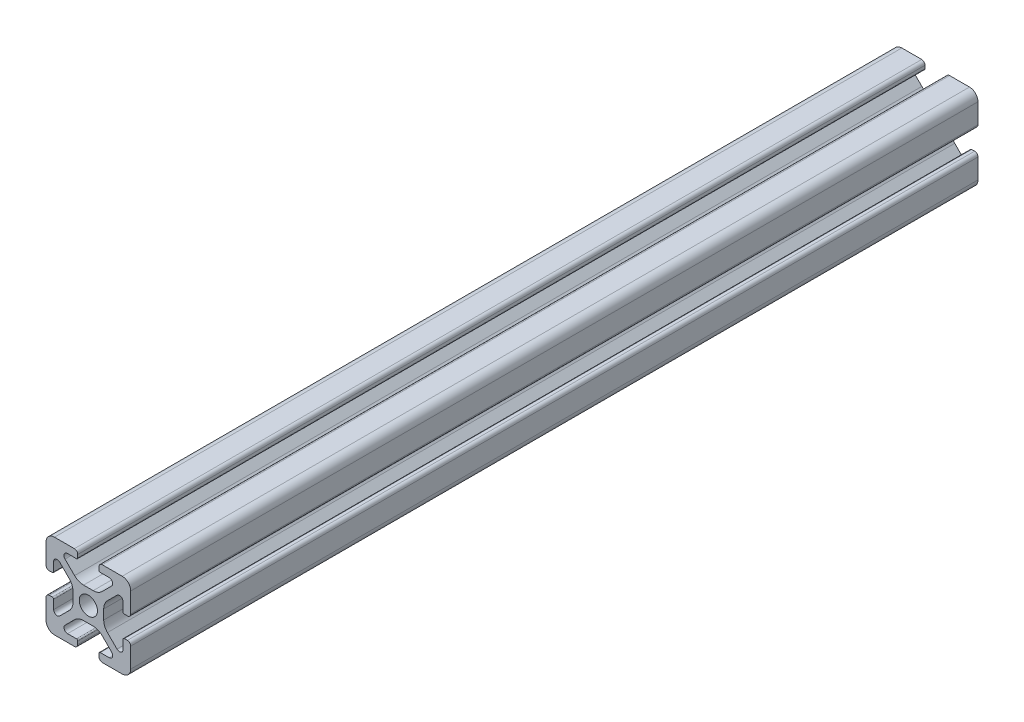
SolidWorks part; units mm, degrees
material "6061 Alloy"
ref_plane "Front Plane" through (0, 0, 0) normal (0, 0, 1) x (1, 0, 0)
ref_plane "Top Plane" through (0, 0, 0) normal (0, 1, 0) x (1, 0, 0)
ref_plane "Right Plane" through (0, 0, 0) normal (1, 0, 0) x (0, 0, -1)
sketch "Sketch1" plane through (0, 0, 0) normal (0, 0, 1) x (1, 0, 0)
  line L2 (-9.9949, 7.9883) -> (-9.9949, 3.2893)
  line L3 (-7.9883, 9.9949) -> (-3.2893, 9.9949)
  line L4 (-2.5019, 9.2075) -> (-2.5019, 8.4963)
  line L5 (-2.8067, 8.1915) -> (-4.9149, 8.1915)
  line L6 (-5.5076, 6.7606) -> (-3.2528, 4.5058)
  line L7 (-6.7606, 5.5076) -> (-4.5058, 3.2528)
  line L8 (-8.1915, 4.9149) -> (-8.1915, 2.8067)
  line L9 (-8.4963, 2.5019) -> (-9.2075, 2.5019)
  line L11 (-1.1334, 3.6279) -> (1.1334, 3.6279)
  line L12 (-3.6279, 1.1334) -> (-3.6279, -1.1334)
  line L13 (8.4963, 2.5019) -> (9.2075, 2.5019)
  line L14 (8.1915, 4.9149) -> (8.1915, 2.8067)
  line L15 (9.9949, 7.9883) -> (9.9949, 3.2893)
  line L16 (7.9883, 9.9949) -> (3.2893, 9.9949)
  line L17 (2.5019, 9.2075) -> (2.5019, 8.4963)
  line L18 (2.8067, 8.1915) -> (4.9149, 8.1915)
  line L19 (3.6279, 1.1334) -> (3.6279, -1.1334)
  line L20 (5.5076, 6.7606) -> (3.2528, 4.5058)
  line L21 (6.7606, 5.5076) -> (4.5058, 3.2528)
  line L22 (-8.4963, -2.5019) -> (-9.2075, -2.5019)
  line L23 (-8.1915, -4.9149) -> (-8.1915, -2.8067)
  line L24 (-6.7606, -5.5076) -> (-4.5058, -3.2528)
  line L25 (-5.5076, -6.7606) -> (-3.2528, -4.5058)
  line L26 (-2.8067, -8.1915) -> (-4.9149, -8.1915)
  line L27 (-2.5019, -9.2075) -> (-2.5019, -8.4963)
  line L28 (-7.9883, -9.9949) -> (-3.2893, -9.9949)
  line L29 (-9.9949, -7.9883) -> (-9.9949, -3.2893)
  line L30 (9.9949, -7.9883) -> (9.9949, -3.2893)
  line L31 (7.9883, -9.9949) -> (3.2893, -9.9949)
  line L32 (2.5019, -9.2075) -> (2.5019, -8.4963)
  line L33 (2.8067, -8.1915) -> (4.9149, -8.1915)
  line L34 (5.5076, -6.7606) -> (3.2528, -4.5058)
  line L35 (6.7606, -5.5076) -> (4.5058, -3.2528)
  line L36 (8.1915, -4.9149) -> (8.1915, -2.8067)
  line L37 (8.4963, -2.5019) -> (9.2075, -2.5019)
  line L38 (-1.1334, -3.6279) -> (1.1334, -3.6279)
  circle A0 centre (0, 0) radius 2.1463
  arc A1 (-9.9949, 7.9883) -> (-7.9883, 9.9949) centre (-7.9883, 7.9883) cw
  arc A2 (-6.7606, 5.5076) -> (-8.1915, 4.9149) centre (-7.3533, 4.9149) ccw
  arc A3 (-4.9149, 8.1915) -> (-5.5076, 6.7606) centre (-4.9149, 7.3533) ccw
  arc A4 (-3.2893, 9.9949) -> (-2.5019, 9.2075) centre (-3.2893, 9.2075) cw
  arc A5 (-9.9949, 3.2893) -> (-9.2075, 2.5019) centre (-9.2075, 3.2893) ccw
  arc A6 (-8.1915, 2.8067) -> (-8.4963, 2.5019) centre (-8.4963, 2.8067) cw
  arc A7 (-2.5019, 8.4963) -> (-2.8067, 8.1915) centre (-2.8067, 8.4963) cw
  arc A8 (-1.1334, 3.6279) -> (-3.2528, 4.5058) centre (-1.1334, 6.6251) cw
  arc A9 (-3.6279, 1.1334) -> (-4.5058, 3.2528) centre (-6.6251, 1.1334) ccw
  arc A10 (8.1915, 2.8067) -> (8.4963, 2.5019) centre (8.4963, 2.8067) ccw
  arc A11 (9.9949, 3.2893) -> (9.2075, 2.5019) centre (9.2075, 3.2893) cw
  arc A12 (9.9949, 7.9883) -> (7.9883, 9.9949) centre (7.9883, 7.9883) ccw
  arc A13 (3.2893, 9.9949) -> (2.5019, 9.2075) centre (3.2893, 9.2075) ccw
  arc A14 (2.5019, 8.4963) -> (2.8067, 8.1915) centre (2.8067, 8.4963) ccw
  arc A15 (1.1334, 3.6279) -> (3.2528, 4.5058) centre (1.1334, 6.6251) ccw
  arc A16 (3.6279, 1.1334) -> (4.5058, 3.2528) centre (6.6251, 1.1334) cw
  arc A17 (6.7606, 5.5076) -> (8.1915, 4.9149) centre (7.3533, 4.9149) cw
  arc A18 (4.9149, 8.1915) -> (5.5076, 6.7606) centre (4.9149, 7.3533) cw
  arc A19 (-3.6279, -1.1334) -> (-4.5058, -3.2528) centre (-6.6251, -1.1334) cw
  arc A20 (-1.1334, -3.6279) -> (-3.2528, -4.5058) centre (-1.1334, -6.6251) ccw
  arc A21 (-2.5019, -8.4963) -> (-2.8067, -8.1915) centre (-2.8067, -8.4963) ccw
  arc A22 (-8.1915, -2.8067) -> (-8.4963, -2.5019) centre (-8.4963, -2.8067) ccw
  arc A23 (-9.9949, -3.2893) -> (-9.2075, -2.5019) centre (-9.2075, -3.2893) cw
  arc A24 (-3.2893, -9.9949) -> (-2.5019, -9.2075) centre (-3.2893, -9.2075) ccw
  arc A25 (-4.9149, -8.1915) -> (-5.5076, -6.7606) centre (-4.9149, -7.3533) cw
  arc A26 (-6.7606, -5.5076) -> (-8.1915, -4.9149) centre (-7.3533, -4.9149) cw
  arc A27 (-9.9949, -7.9883) -> (-7.9883, -9.9949) centre (-7.9883, -7.9883) ccw
  arc A28 (9.9949, -7.9883) -> (7.9883, -9.9949) centre (7.9883, -7.9883) cw
  arc A29 (6.7606, -5.5076) -> (8.1915, -4.9149) centre (7.3533, -4.9149) ccw
  arc A30 (4.9149, -8.1915) -> (5.5076, -6.7606) centre (4.9149, -7.3533) ccw
  arc A31 (3.2893, -9.9949) -> (2.5019, -9.2075) centre (3.2893, -9.2075) cw
  arc A32 (9.9949, -3.2893) -> (9.2075, -2.5019) centre (9.2075, -3.2893) ccw
  arc A33 (8.1915, -2.8067) -> (8.4963, -2.5019) centre (8.4963, -2.8067) cw
  arc A34 (2.5019, -8.4963) -> (2.8067, -8.1915) centre (2.8067, -8.4963) cw
  arc A35 (1.1334, -3.6279) -> (3.2528, -4.5058) centre (1.1334, -6.6251) cw
  arc A36 (3.6279, -1.1334) -> (4.5058, -3.2528) centre (6.6251, -1.1334) ccw
extrude "Boss-Extrude1" add sketch "Sketch1" along normal mid plane 200
